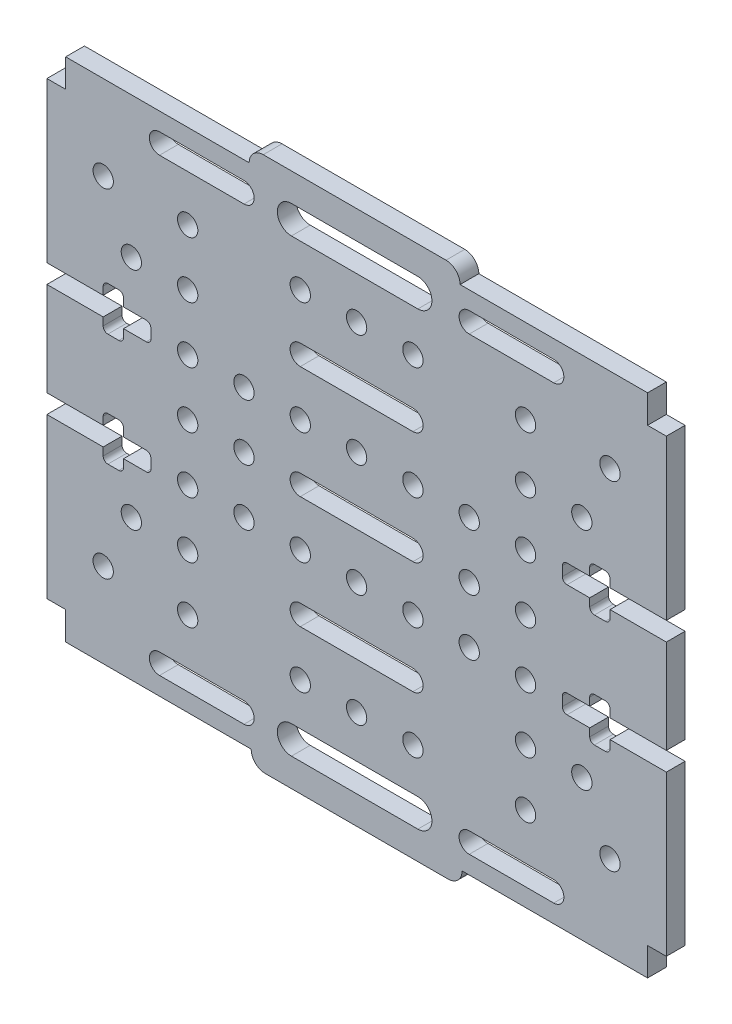
SolidWorks part; units mm, degrees
ref_plane "Alzado" through (0, 0, 0) normal (0, 0, 1) x (1, 0, 0)
ref_plane "Planta" through (0, 0, 0) normal (0, 1, 0) x (1, 0, 0)
ref_plane "Vista lateral" through (0, 0, 0) normal (1, 0, 0) x (0, 0, -1)
sketch "Model" plane through (0, 0, 0) normal (0, 0, 1) x (1, 0, 0)
  line L0 (-1386.7269, 396.9082) -> (-1386.7269, 392.4082)
  line L1 (-1383.7269, 392.4082) -> (-1386.7269, 392.4082)
  line L2 (-1383.7269, 320.4082) -> (-1386.7269, 320.4082)
  line L3 (-1386.7269, 320.4082) -> (-1386.7269, 315.9082)
  line L4 (-1386.7269, 396.9082) -> (-1416.6915, 396.9082)
  line L5 (-1479.7269, 396.9082) -> (-1479.7269, 392.4082)
  line L6 (-1479.7269, 392.4082) -> (-1482.7269, 392.4082)
  line L7 (-1482.7269, 392.4082) -> (-1482.7269, 366.9082)
  line L8 (-1482.7269, 320.4082) -> (-1479.7269, 320.4082)
  line L9 (-1479.7269, 320.4082) -> (-1479.7269, 315.9082)
  line L10 (-1416.374, 315.9082) -> (-1386.7269, 315.9082)
  line L11 (-1383.7269, 345.9082) -> (-1383.7269, 320.4082)
  line L12 (-1443.6474, 394.6582) -> (-1423.4415, 394.6582)
  line L13 (-1443.6474, 390.1582) -> (-1423.4415, 390.1582)
  line L14 (-1443.6445, 322.6582) -> (-1423.4386, 322.6582)
  line L15 (-1443.6445, 318.1582) -> (-1423.4386, 318.1582)
  line L16 (-1442.2299, 376.0381) -> (-1424.2299, 376.0381)
  line L17 (-1424.2299, 372.7881) -> (-1442.2299, 372.7881)
  line L18 (-1442.2299, 358.0381) -> (-1424.2299, 358.0381)
  line L19 (-1424.2299, 354.7881) -> (-1442.2299, 354.7881)
  line L22 (-1442.2299, 340.0381) -> (-1424.2299, 340.0381)
  line L23 (-1424.2299, 336.7881) -> (-1442.2299, 336.7881)
  line L24 (-1464.7274, 322.0332) -> (-1451.2274, 322.0332)
  line L25 (-1464.7274, 318.7832) -> (-1451.2274, 318.7832)
  line L26 (-1415.2274, 322.0332) -> (-1401.7274, 322.0332)
  line L27 (-1415.2274, 318.7832) -> (-1401.7274, 318.7832)
  line L28 (-1415.2299, 394.0381) -> (-1401.7299, 394.0381)
  line L29 (-1401.7299, 390.7881) -> (-1415.2299, 390.7881)
  line L30 (-1464.7296, 394.0381) -> (-1451.2299, 394.0381)
  line L31 (-1451.2299, 390.7881) -> (-1464.7296, 390.7881)
  line L32 (-1383.7269, 363.9082) -> (-1392.7219, 363.9082)
  line L33 (-1392.7219, 366.9082) -> (-1383.7269, 366.9082)
  line L34 (-1399.5969, 366.9082) -> (-1395.9719, 366.9082)
  line L35 (-1395.9719, 363.9082) -> (-1399.5969, 363.9082)
  line L36 (-1400.3469, 364.6582) -> (-1400.3469, 366.1582)
  line L37 (-1466.8569, 363.9082) -> (-1470.4819, 363.9082)
  line L38 (-1470.4819, 366.9082) -> (-1466.8569, 366.9082)
  line L39 (-1466.1069, 366.1582) -> (-1466.1069, 364.6582)
  line L40 (-1472.9819, 368.9082) -> (-1471.2319, 368.9082)
  line L41 (-1471.2319, 361.9082) -> (-1472.9819, 361.9082)
  line L42 (-1473.7319, 366.9082) -> (-1473.7319, 368.1582)
  line L43 (-1470.4819, 366.9082) -> (-1470.4819, 368.1582)
  line L44 (-1473.7319, 363.9082) -> (-1473.7319, 362.6582)
  line L45 (-1470.4819, 363.9082) -> (-1470.4819, 362.6582)
  line L46 (-1395.2219, 368.9082) -> (-1393.4719, 368.9082)
  line L47 (-1393.4719, 361.9082) -> (-1395.2219, 361.9082)
  line L48 (-1395.9719, 366.9082) -> (-1395.9719, 368.1582)
  line L49 (-1392.7219, 366.9082) -> (-1392.7219, 368.1582)
  line L50 (-1395.9719, 363.9082) -> (-1395.9719, 362.6582)
  line L51 (-1392.7219, 363.9082) -> (-1392.7219, 362.6582)
  line L52 (-1482.7269, 366.9082) -> (-1473.7319, 366.9082)
  line L53 (-1482.7269, 363.9082) -> (-1473.7319, 363.9082)
  line L54 (-1383.7269, 345.9082) -> (-1392.7219, 345.9082)
  line L55 (-1392.7219, 348.9082) -> (-1383.7269, 348.9082)
  line L56 (-1399.5969, 348.9082) -> (-1395.9719, 348.9082)
  line L57 (-1395.9719, 345.9082) -> (-1399.5969, 345.9082)
  line L58 (-1400.3469, 346.6582) -> (-1400.3469, 348.1582)
  line L59 (-1466.8569, 345.9082) -> (-1470.4819, 345.9082)
  line L60 (-1470.4819, 348.9082) -> (-1466.8569, 348.9082)
  line L61 (-1466.1069, 348.1582) -> (-1466.1069, 346.6582)
  line L62 (-1472.9819, 350.9082) -> (-1471.2319, 350.9082)
  line L63 (-1471.2319, 343.9082) -> (-1472.9819, 343.9082)
  line L64 (-1473.7319, 348.9082) -> (-1473.7319, 350.1582)
  line L65 (-1470.4819, 348.9082) -> (-1470.4819, 350.1582)
  line L66 (-1473.7319, 345.9082) -> (-1473.7319, 344.6582)
  line L67 (-1470.4819, 345.9082) -> (-1470.4819, 344.6582)
  line L68 (-1395.2219, 350.9082) -> (-1393.4719, 350.9082)
  line L69 (-1393.4719, 343.9082) -> (-1395.2219, 343.9082)
  line L70 (-1395.9719, 348.9082) -> (-1395.9719, 350.1582)
  line L71 (-1392.7219, 348.9082) -> (-1392.7219, 350.1582)
  line L72 (-1395.9719, 345.9082) -> (-1395.9719, 344.6582)
  line L73 (-1392.7219, 345.9082) -> (-1392.7219, 344.6582)
  line L74 (-1482.7269, 348.9082) -> (-1473.7319, 348.9082)
  line L75 (-1482.7269, 345.9082) -> (-1473.7319, 345.9082)
  line L76 (-1383.7269, 392.4082) -> (-1383.7269, 366.9082)
  line L77 (-1383.7269, 363.9082) -> (-1383.7269, 348.9082)
  line L78 (-1482.7269, 345.9082) -> (-1482.7269, 320.4082)
  line L79 (-1482.7269, 363.9082) -> (-1482.7269, 348.9082)
  line L80 (-1448.1474, 399.1582) -> (-1418.9415, 399.1582)
  line L81 (-1450.3974, 396.9082) -> (-1479.7269, 396.9082)
  line L82 (-1447.8298, 313.6582) -> (-1418.624, 313.6582)
  line L83 (-1479.7269, 315.9082) -> (-1450.0798, 315.9082)
  arc A0 (-1443.6474, 394.6582) -> (-1443.6474, 390.1582) centre (-1443.6474, 392.4082) ccw
  arc A1 (-1423.4415, 390.1582) -> (-1423.4415, 394.6582) centre (-1423.4415, 392.4082) ccw
  arc A2 (-1443.6445, 322.6582) -> (-1443.6445, 318.1582) centre (-1443.6445, 320.4082) ccw
  arc A3 (-1423.4386, 318.1582) -> (-1423.4386, 322.6582) centre (-1423.4386, 320.4082) ccw
  circle A4 centre (-1433.2299, 365.4131) radius 1.625
  circle A5 centre (-1433.2299, 347.4131) radius 1.625
  circle A6 centre (-1433.2299, 329.4131) radius 1.625
  circle A7 centre (-1433.2299, 383.4131) radius 1.625
  circle A8 centre (-1460.2299, 374.4131) radius 1.625
  circle A9 centre (-1460.2299, 365.4131) radius 1.625
  circle A10 centre (-1460.2299, 356.4131) radius 1.625
  circle A11 centre (-1460.2299, 347.4131) radius 1.625
  circle A12 centre (-1460.2299, 338.4131) radius 1.625
  circle A13 centre (-1460.2299, 329.4131) radius 1.625
  circle A14 centre (-1460.2299, 383.4131) radius 1.625
  circle A15 centre (-1406.2299, 374.4131) radius 1.625
  circle A16 centre (-1406.2299, 365.4131) radius 1.625
  circle A17 centre (-1406.2299, 356.4131) radius 1.625
  circle A18 centre (-1406.2299, 347.4131) radius 1.625
  circle A19 centre (-1406.2299, 338.4131) radius 1.625
  circle A20 centre (-1406.2299, 329.4131) radius 1.625
  circle A21 centre (-1406.2299, 383.4131) radius 1.625
  arc A22 (-1442.2299, 376.0381) -> (-1442.2299, 372.7881) centre (-1442.2299, 374.4131) ccw
  arc A23 (-1424.2299, 372.7881) -> (-1424.2299, 376.0381) centre (-1424.2299, 374.4131) ccw
  arc A24 (-1442.2299, 358.0381) -> (-1442.2299, 354.7881) centre (-1442.2299, 356.4131) ccw
  arc A25 (-1424.2299, 354.7881) -> (-1424.2299, 358.0381) centre (-1424.2299, 356.4131) ccw
  arc A28 (-1442.2299, 340.0381) -> (-1442.2299, 336.7881) centre (-1442.2299, 338.4131) ccw
  arc A29 (-1424.2299, 336.7881) -> (-1424.2299, 340.0381) centre (-1424.2299, 338.4131) ccw
  arc A30 (-1464.7296, 394.0381) -> (-1464.7296, 390.7881) centre (-1464.7296, 392.4131) ccw
  arc A31 (-1451.2299, 390.7881) -> (-1451.2299, 394.0381) centre (-1451.2299, 392.4131) ccw
  arc A32 (-1401.7299, 390.7881) -> (-1401.7299, 394.0381) centre (-1401.7299, 392.4131) ccw
  arc A33 (-1415.2299, 394.0381) -> (-1415.2299, 390.7881) centre (-1415.2299, 392.4131) ccw
  arc A34 (-1401.7274, 318.7832) -> (-1401.7274, 322.0332) centre (-1401.7274, 320.4082) ccw
  arc A35 (-1415.2274, 322.0332) -> (-1415.2274, 318.7832) centre (-1415.2274, 320.4082) ccw
  arc A36 (-1451.2274, 318.7832) -> (-1451.2274, 322.0332) centre (-1451.2274, 320.4082) ccw
  arc A37 (-1464.7274, 322.0332) -> (-1464.7274, 318.7832) centre (-1464.7274, 320.4082) ccw
  circle A38 centre (-1424.2299, 383.4131) radius 1.625
  circle A39 centre (-1442.2299, 383.4131) radius 1.625
  circle A40 centre (-1424.2299, 365.4131) radius 1.625
  circle A41 centre (-1442.2299, 365.4131) radius 1.625
  circle A42 centre (-1424.2299, 347.4131) radius 1.625
  circle A43 centre (-1442.2299, 347.4131) radius 1.625
  circle A44 centre (-1424.2299, 329.4131) radius 1.625
  circle A45 centre (-1442.2299, 329.4131) radius 1.625
  circle A46 centre (-1415.2299, 365.4131) radius 1.625
  circle A47 centre (-1415.2299, 356.4131) radius 1.625
  circle A48 centre (-1415.2299, 347.4131) radius 1.625
  circle A49 centre (-1451.2299, 365.4131) radius 1.625
  circle A50 centre (-1451.2299, 356.4131) radius 1.625
  circle A51 centre (-1451.2299, 347.4131) radius 1.625
  circle A52 centre (-1473.7296, 383.4131) radius 1.625
  circle A53 centre (-1392.7299, 383.4131) radius 1.625
  circle A54 centre (-1473.7296, 329.4131) radius 1.625
  circle A55 centre (-1392.7299, 329.4131) radius 1.625
  arc A56 (-1466.1069, 366.1582) -> (-1466.8569, 366.9082) centre (-1466.8569, 366.1582) ccw
  arc A57 (-1466.8569, 363.9082) -> (-1466.1069, 364.6582) centre (-1466.8569, 364.6582) ccw
  arc A58 (-1399.5969, 366.9082) -> (-1400.3469, 366.1582) centre (-1399.5969, 366.1582) ccw
  arc A59 (-1400.3469, 364.6582) -> (-1399.5969, 363.9082) centre (-1399.5969, 364.6582) ccw
  arc A60 (-1472.9819, 368.9082) -> (-1473.7319, 368.1582) centre (-1472.9819, 368.1582) ccw
  arc A61 (-1470.4819, 368.1582) -> (-1471.2319, 368.9082) centre (-1471.2319, 368.1582) ccw
  arc A62 (-1471.2319, 361.9082) -> (-1470.4819, 362.6582) centre (-1471.2319, 362.6582) ccw
  arc A63 (-1473.7319, 362.6582) -> (-1472.9819, 361.9082) centre (-1472.9819, 362.6582) ccw
  arc A64 (-1395.2219, 368.9082) -> (-1395.9719, 368.1582) centre (-1395.2219, 368.1582) ccw
  arc A65 (-1392.7219, 368.1582) -> (-1393.4719, 368.9082) centre (-1393.4719, 368.1582) ccw
  arc A66 (-1393.4719, 361.9082) -> (-1392.7219, 362.6582) centre (-1393.4719, 362.6582) ccw
  arc A67 (-1395.9719, 362.6582) -> (-1395.2219, 361.9082) centre (-1395.2219, 362.6582) ccw
  arc A68 (-1466.1069, 348.1582) -> (-1466.8569, 348.9082) centre (-1466.8569, 348.1582) ccw
  arc A69 (-1466.8569, 345.9082) -> (-1466.1069, 346.6582) centre (-1466.8569, 346.6582) ccw
  arc A70 (-1399.5969, 348.9082) -> (-1400.3469, 348.1582) centre (-1399.5969, 348.1582) ccw
  arc A71 (-1400.3469, 346.6582) -> (-1399.5969, 345.9082) centre (-1399.5969, 346.6582) ccw
  arc A72 (-1472.9819, 350.9082) -> (-1473.7319, 350.1582) centre (-1472.9819, 350.1582) ccw
  arc A73 (-1470.4819, 350.1582) -> (-1471.2319, 350.9082) centre (-1471.2319, 350.1582) ccw
  arc A74 (-1471.2319, 343.9082) -> (-1470.4819, 344.6582) centre (-1471.2319, 344.6582) ccw
  arc A75 (-1473.7319, 344.6582) -> (-1472.9819, 343.9082) centre (-1472.9819, 344.6582) ccw
  arc A76 (-1395.2219, 350.9082) -> (-1395.9719, 350.1582) centre (-1395.2219, 350.1582) ccw
  arc A77 (-1392.7219, 350.1582) -> (-1393.4719, 350.9082) centre (-1393.4719, 350.1582) ccw
  arc A78 (-1393.4719, 343.9082) -> (-1392.7219, 344.6582) centre (-1393.4719, 344.6582) ccw
  arc A79 (-1395.9719, 344.6582) -> (-1395.2219, 343.9082) centre (-1395.2219, 344.6582) ccw
  arc A80 (-1448.1474, 399.1582) -> (-1450.3974, 396.9082) centre (-1448.1474, 396.9082) ccw
  arc A81 (-1416.6915, 396.9082) -> (-1418.9415, 399.1582) centre (-1418.9415, 396.9082) ccw
  arc A82 (-1450.0798, 315.9082) -> (-1447.8298, 313.6582) centre (-1447.8298, 315.9082) ccw
  arc A83 (-1418.624, 313.6582) -> (-1416.374, 315.9082) centre (-1418.624, 315.9082) ccw
  circle A84 centre (-1469.2299, 374.4131) radius 1.625
  circle A85 centre (-1469.2299, 338.4131) radius 1.625
  circle A86 centre (-1397.2299, 374.4131) radius 1.625
  circle A87 centre (-1397.2299, 338.4131) radius 1.625
extrude "Saliente-Extruir1" add sketch "Model" along normal blind 3
